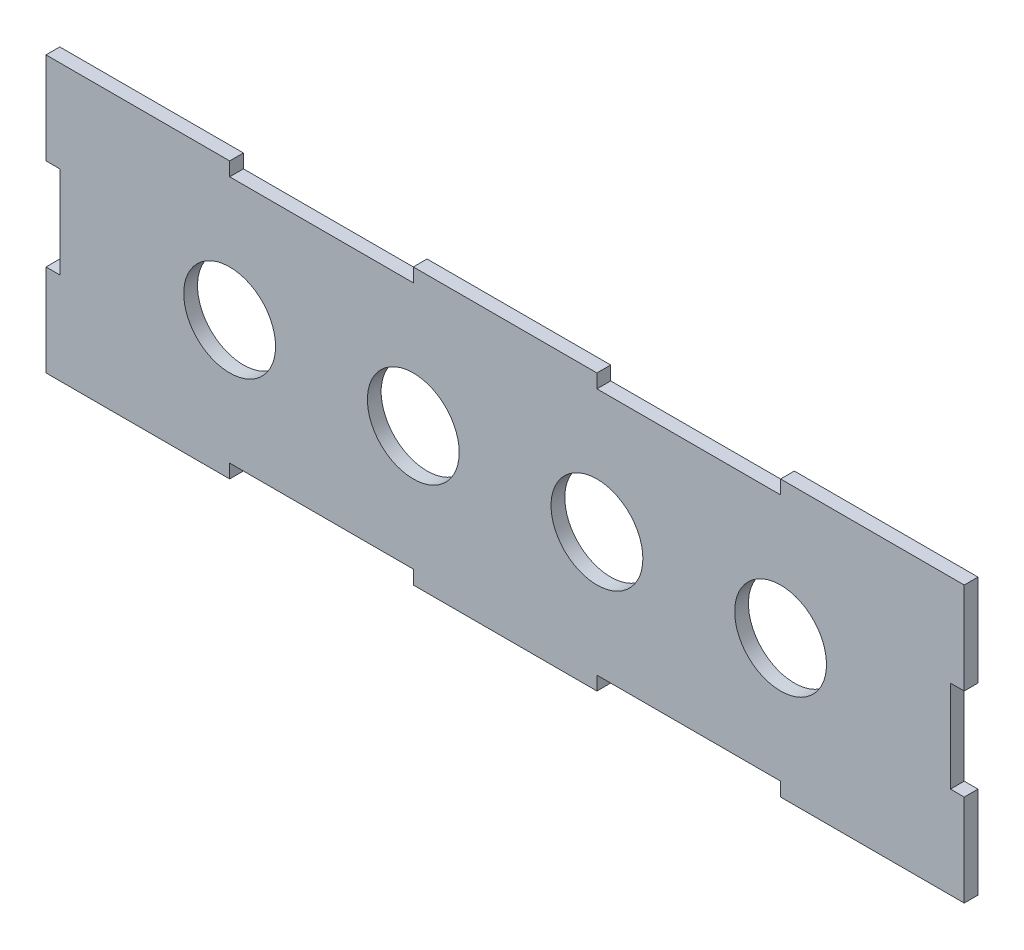
SolidWorks part; units mm, degrees
material "Acrylic (Medium-high impact)"
ref_plane "Alzado" through (0, 0, 0) normal (0, 0, 1) x (1, 0, 0)
ref_plane "Planta" through (0, 0, 0) normal (0, 1, 0) x (1, 0, 0)
ref_plane "Vista lateral" through (0, 0, 0) normal (1, 0, 0) x (0, 0, -1)
sketch "Sketch1" plane through (0, 0, 0) normal (0, 0, 1) x (1, 0, 0)
  line L0 (-90, 30) -> (-50, 30) construction
  line L1 (-90, 30) -> (-50, 30)
  line L2 (-90, 30) -> (-90, 10)
  line L3 (-90, -30) -> (-50, -30)
  line L4 (110, 30) -> (110, 10)
  line L5 (-50, 30) -> (-50, 27)
  line L6 (-50, 27) -> (-10, 27)
  line L7 (-10, 27) -> (-10, 30)
  line L8 (-10, 30) -> (30, 30)
  line L9 (30, 30) -> (30, 27)
  line L10 (30, 27) -> (70, 27)
  line L11 (70, 27) -> (70, 30)
  line L12 (70, 30) -> (71.4009, 30)
  line L13 (-10, 30) -> (30, 30)
  line L14 (70, 30) -> (110, 30)
  line L15 (-87, 0) -> (107, 0) construction
  line L16 (-90, -30) -> (-50, -30) construction
  line L17 (70, -30) -> (110, -30)
  line L18 (-10, -30) -> (30, -30)
  line L19 (70, -30) -> (71.4009, -30)
  line L20 (70, -27) -> (70, -30)
  line L21 (30, -27) -> (70, -27)
  line L22 (30, -30) -> (30, -27)
  line L23 (-10, -30) -> (30, -30)
  line L24 (-10, -27) -> (-10, -30)
  line L25 (-50, -27) -> (-10, -27)
  line L26 (-50, -30) -> (-50, -27)
  line L27 (-90, -30) -> (-50, -30)
  line L28 (-10, -30) -> (30, -30)
  line L29 (70, -30) -> (110, -30)
  line L30 (110, 30) -> (110, 10)
  line L31 (110, 10) -> (107, 10)
  line L32 (107, 10) -> (107, -10)
  line L33 (107, -10) -> (110, -10)
  line L34 (110, -10) -> (110, -30)
  line L35 (10, 30) -> (10, -30) construction
  line L36 (108, 0) -> (-87, 0) construction
  line L37 (-90, -10) -> (-90, -30)
  line L38 (-87, -10) -> (-90, -10)
  line L39 (-87, 10) -> (-87, -10)
  line L40 (-90, 10) -> (-87, 10)
  line L41 (-90, 30) -> (-90, 10)
  line L42 (-90, 30) -> (-90, 10)
  line L43 (-90, -10) -> (-90, -30)
  point P0 (0, 0)
  dimension "D1" = 60
  dimension "D2" = 200
  dimension "D4" = 3
  dimension "D5" = 40
  dimension "D6" = 40
  dimension "D7" = 3
  dimension "D8" = 40
  dimension "D9" = 3
  dimension "D10" = 20
  dimension "D11" = 20
extrude "Boss-Extrude1" add sketch "Sketch1" along normal blind 3 contours L2 L40 L39 L38 L37 L3 L26 L25 L24 L18 L22 L21 L20 L17 L34 L33 L32 L31 L4 L14 L12 L11 L10 L9 L8 L7 L6 L5 L1
sketch "Sketch2" plane through (0, 0, 3) normal (0, 0, 1) x (1, 0, 0)
  line L0 (-50, 27) -> (-50, -27) construction
  line L1 (-10, 27) -> (-10, -25) construction
  line L2 (10, 38.3579) -> (10, -37.7096) construction
  line L3 (-99.4551, 0) -> (120.1034, 0) construction
  line L4 (70, 27) -> (70, -27) construction
  line L5 (30, 27) -> (30, -25) construction
  circle A0 centre (-50, 0) radius 10
  circle A1 centre (-10, 0) radius 10
  circle A2 centre (30, 0) radius 10
  circle A3 centre (70, 0) radius 10
  dimension "D1" = 4
extrude "Cut-Extrude1" cut sketch "Sketch2" against normal through all
